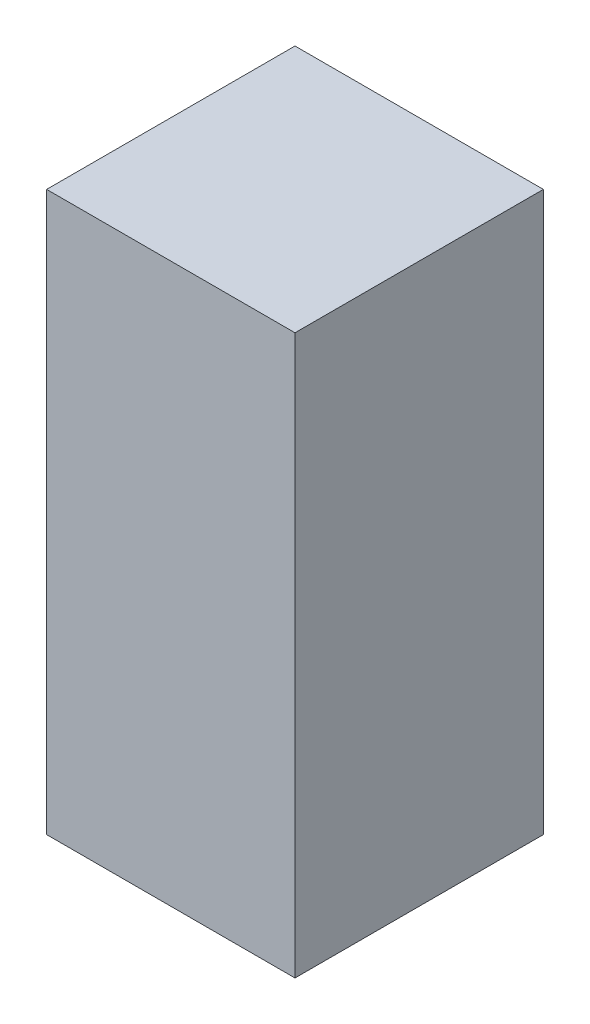
SolidWorks part; units mm, degrees
ref_plane "Front Plane" through (0, 0, 0) normal (0, 0, 1) x (1, 0, 0)
ref_plane "Top Plane" through (0, 0, 0) normal (0, 1, 0) x (1, 0, 0)
ref_plane "Right Plane" through (0, 0, 0) normal (1, 0, 0) x (0, 0, -1)
other "Configuration Table"
sketch "Sketch1" plane through (0, 0, 0) normal (0, 0, 1) x (1, 0, 0)
  line L1 (502.5, 552) -> (522.5, 552)
  line L2 (502.5, 552) -> (502.5, 597)
  line L3 (502.5, 597) -> (522.5, 597)
  line L4 (522.5, 552) -> (522.5, 597)
extrude "PACK_kose_plowu_2_1" add sketch "Sketch1" against normal blind 20 from offset 552.5 separate body
